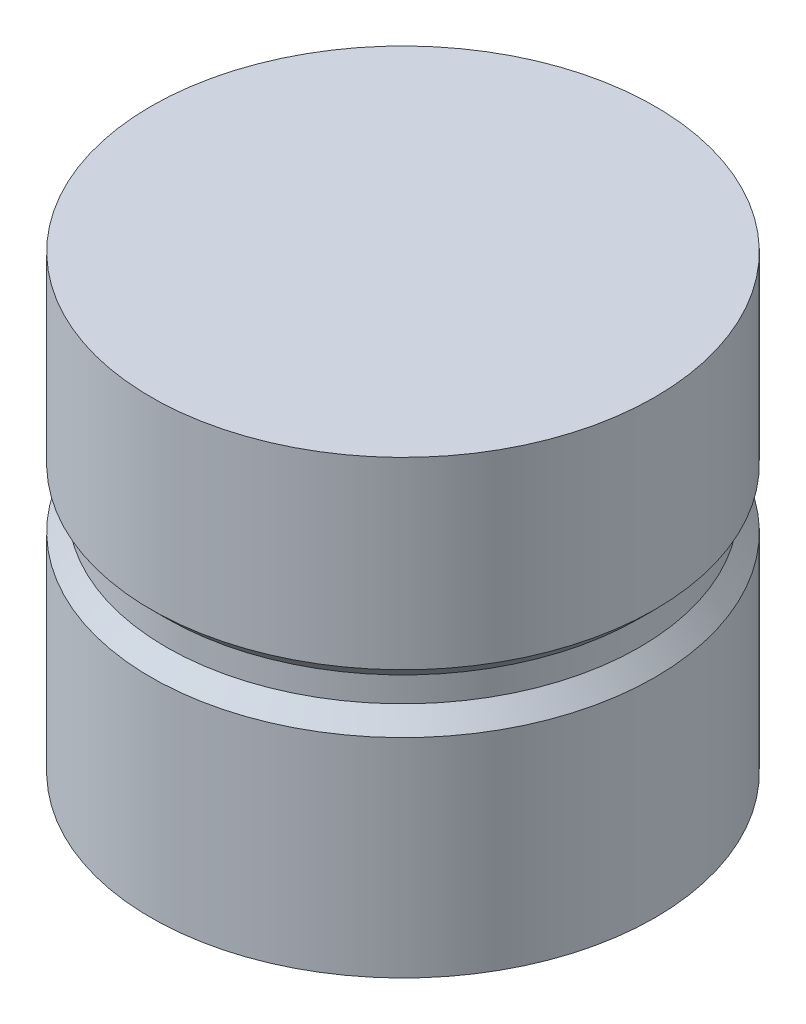
SolidWorks part; units mm, degrees
material "Легированная сталь"
ref_plane "Спереди" through (0, 0, 0) normal (0, 0, 1) x (1, 0, 0)
ref_plane "Сверху" through (0, 0, 0) normal (0, 1, 0) x (1, 0, 0)
ref_plane "Справа" through (0, 0, 0) normal (1, 0, 0) x (0, 0, -1)
sketch "Эскиз1" plane through (0, 0, 0) normal (0, 0, 1) x (1, 0, 0)
  line L0 (0, 32.2) -> (0, 34)
  line L1 (0, 34) -> (19, 34)
  line L2 (19, 34) -> (19, 20.1304)
  line L3 (19, 0) -> (17.2, 0)
  line L4 (17.2, 0) -> (17.2, 15.7)
  line L5 (17.2, 32.2) -> (0, 32.2)
  line L6 (19, 20.1304) -> (17.8447, 18.9751)
  line L7 (17.8447, 18.9751) -> (17.8447, 17.0899)
  line L8 (17.8447, 17.0899) -> (19, 15.7)
  line L9 (17.2, 20.1304) -> (16.0447, 18.9751)
  line L10 (16.0447, 18.9751) -> (16.0447, 17.0899)
  line L11 (16.0447, 17.0899) -> (17.2, 15.7)
  line L12 (17.2, 20.1304) -> (17.2, 32.2)
  line L13 (19, 15.7) -> (19, 0)
  point P16 (0, 0)
  point P17 (0, 0)
  point P18 (0, 0)
  dimension "D1" = 1.8
  dimension "D3" = 19
  dimension "D4" = 34
revolve "Повернуть1" add sketch "Эскиз1" angle 360 about L0
